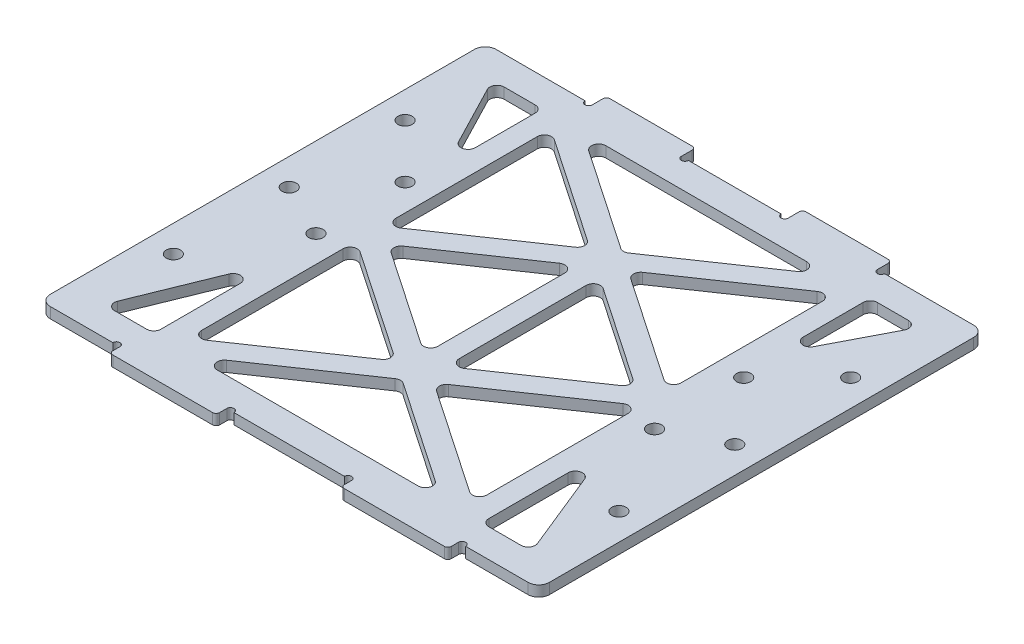
SolidWorks part; units mm, degrees
material "Thornel Mat VMA"
ref_plane "前视基准面" through (0, 0, 0) normal (0, 0, 1) x (1, 0, 0)
ref_plane "上视基准面" through (0, 0, 0) normal (0, 1, 0) x (1, 0, 0)
ref_plane "右视基准面" through (0, 0, 0) normal (1, 0, 0) x (0, 0, -1)
sketch "草图1" plane through (0, 0, 0) normal (0, 1, 0) x (1, 0, 0)
  line L0 (0, -55) -> (0, 55) construction
  line L29 (-17.5, 0) -> (17.5, 0)
  line L31 (-47.5, 0) -> (-47.5, -3)
  line L32 (-47.5, -3) -> (-17.5, -3)
  line L33 (-17.5, 0) -> (-17.5, -3)
  line L34 (17.5, 0) -> (17.5, -3)
  line L35 (47.5, -3) -> (17.5, -3)
  line L36 (47.5, 0) -> (47.5, -3)
  line L42 (47.5, 80) -> (-47.5, 80) construction
  line L43 (47.5, 80) -> (47.5, 55) construction
  line L44 (47.5, 55) -> (-47.5, 55) construction
  line L45 (-47.5, 80) -> (-47.5, 55) construction
  line L52 (-15, 125) -> (15, 125)
  line L63 (-70, 125) -> (-40, 125)
  line L64 (-40, 125) -> (-40, 129)
  line L65 (-40, 129) -> (-15, 129)
  line L66 (-15, 125) -> (-15, 129)
  line L67 (15, 125) -> (15, 129)
  line L68 (15, 129) -> (40, 129)
  line L69 (40, 129) -> (40, 125)
  line L70 (40, 125) -> (70, 125)
  line L72 (0, 55) -> (0, 0) construction
  line L82 (-70, 0) -> (-47.5, 0)
  line L87 (47.5, 0) -> (70, 0)
  line L90 (-18, 113) -> (18, 113) construction
  line L91 (-18, 113) -> (-18, 77) construction
  line L92 (-18, 77) -> (18, 77) construction
  line L93 (18, 113) -> (18, 77) construction
  line L94 (-70, 125) -> (-70, 0)
  line L95 (70, 125) -> (70, 0)
  line L96 (-62.5, 95) -> (-62.5, 30) construction
  circle A2 centre (47.5, 80) radius 2
  circle A3 centre (47.5, 55) radius 2
  circle A4 centre (-47.5, 55) radius 2
  circle A5 centre (-47.5, 80) radius 2
  circle A12 centre (18, 113) radius 1.5 construction
  circle A13 centre (18, 77) radius 1.5 construction
  circle A14 centre (-18, 77) radius 1.5 construction
  circle A15 centre (-18, 113) radius 1.5 construction
  circle A16 centre (-62.5, 30) radius 2
  circle A17 centre (-62.5, 62.5) radius 2
  circle A18 centre (-62.5, 95) radius 2
  circle A19 centre (62.5, 95) radius 2
  circle A20 centre (62.5, 62.5) radius 2
  circle A21 centre (62.5, 30) radius 2
  point P57 (0, 125)
  dimension "D16" = 30
  dimension "D20" = 4
  dimension "D31" = 12
  dimension "D32" = 3
  dimension "D43" = 4
  dimension "D13" = 65
  dimension "D14" = 4
  dimension "D15" = 125
  dimension "D5" = 3
  dimension "D6" = 30
  dimension "D7" = 35
  dimension "D8" = 140
  dimension "D9" = 7.5
  dimension "D10" = 25
  dimension "D11" = 30
  dimension "D12" = 45
  dimension "D18" = 25
  dimension "D19" = 95
  dimension "D30" = 36
extrude "凸台-拉伸1" add sketch "草图1" along normal blind 3
sketch "草图3" plane through (0, 3, 0) normal (0, 1, 0) x (1, 0, 0)
  line L10 (0, -1.65) -> (0, 1.65) construction
  line L11 (-60, 117) -> (-46, 90)
  line L16 (46, 8) -> (46, 42.5)
  line L26 (-40, 117) -> (40, 117)
  line L27 (60, 8) -> (46, 8)
  line L40 (46, 42.5) -> (60, 8)
  line L41 (-40, 117) -> (-40, 8)
  line L42 (-40, 8) -> (40, 8)
  line L44 (-46, 90) -> (-46, 117)
  line L45 (-46, 117) -> (-60, 117)
  line L47 (-46, 42.5) -> (-60, 8)
  line L48 (-60, 8) -> (-46, 8)
  line L49 (-46, 8) -> (-46, 42.5)
  line L51 (-17.5, 0) -> (17.5, 0) construction
  line L52 (15, 125) -> (-15, 125) construction
  line L53 (-70, 125) -> (-70, 0) construction
  line L54 (46, 117) -> (60, 117)
  line L55 (46, 90) -> (46, 117)
  line L56 (40, 117) -> (40, 8)
  line L57 (60, 117) -> (46, 90)
  circle A4 centre (-47.5, 80) radius 2 construction
  circle A5 centre (-47.5, 55) radius 2 construction
  dimension "D1" = 7.5
  dimension "D8" = 10
  dimension "D2" = 6
  dimension "D3" = 6
  dimension "D4" = 8
  dimension "D5" = 8
  dimension "D7" = 10
  dimension "D9" = 12.5
  dimension "D6" = 10
extrude "切除-拉伸2" cut sketch "草图3" against normal through all
sketch "草图2" plane through (0, 3, 0) normal (0, 1, 0) x (1, 0, 0)
  line L0 (15, 125) -> (-15, 125) construction
  line L1 (70, 125) -> (40, 125) construction
  line L13 (-17.5, 0) -> (17.5, 0) construction
  line L14 (-70, 0) -> (-47.5, 0) construction
  line L20 (-40, 125) -> (-70, 125) construction
  line L26 (15, 125) -> (-15, 125) construction
  line L30 (47.5, 0) -> (70, 0) construction
  circle A31 centre (-48.5, 0) radius 1
  circle A32 centre (-16.5, 0) radius 1
  circle A33 centre (16.5, 0) radius 1
  circle A37 centre (14, 125) radius 1
  circle A38 centre (-41, 125) radius 1
  circle A39 centre (-14, 125) radius 1
  circle A40 centre (41, 125) radius 1
  circle A65 centre (48.5, 0) radius 1
  dimension "D1" = 2
extrude "切除-拉伸1" cut sketch "草图2" against normal through all
sketch "草图5" plane through (0, 3, 0) normal (0, 1, 0) x (1, 0, 0)
  line L0 (-40, 117) -> (-40, 8) construction
  line L1 (40, 8) -> (40, 117) construction
  line L52 (-40, 117) -> (40, 62.5)
  line L54 (40, 62.5) -> (-40, 8)
  line L55 (40, 8) -> (-40, 62.5)
  line L57 (-40, 62.5) -> (40, 117)
  line L58 (0, 89.75) -> (0, 35.25)
extrude "拉伸-薄壁1" add sketch "草图5" against normal up to surface (3 mm away) thin up to face at (50.6667, 0, -108) thin type mid plane wall 6
fillet "圆角1" radius 2 36 edges at (40, 1.5, -58.87) (40, 1.5, -11.63) (34.6716, 1.5, -8) (-34.6716, 1.5, -8) (-40, 1.5, -11.63) (-40, 1.5, -58.87) (-40, 1.5, -66.13) (-34.6716, 1.5, -117) (34.6716, 1.5, -117) (40, 1.5, -113.37) (40, 1.5, -66.13) (-46, 1.5, -90) (-60, 1.5, -117) (-46, 1.5, -117) (-60, 1.5, -8) (-46, 1.5, -42.5) (-46, 1.5, -8) (46, 1.5, -42.5) (60, 1.5, -8) (46, 1.5, -8) (60, 1.5, -117) (46, 1.5, -90) (46, 1.5, -117) (-40, 1.5, -113.37) (34.6716, 1.5, -62.5) (3, 1.5, -84.0762) (3, 1.5, -40.9238) (-34.6716, 1.5, -62.5) (-3, 1.5, -40.9238) (5.3284, 1.5, -89.75) (0, 1.5, -31.62) (0, 1.5, -93.38) (-5.3284, 1.5, -35.25) (-5.3284, 1.5, -89.75) (5.3284, 1.5, -35.25) (-3, 1.5, -84.0762)
fillet "圆角2" radius 1 8 edges at (-47.5, 1.5, 3) (-17.5, 1.5, 3) (17.5, 1.5, 3) (47.5, 1.5, 3) (40, 1.5, -129) (15, 1.5, -129) (-15, 1.5, -129) (-40, 1.5, -129)
fillet "圆角3" radius 3 4 edges at (70, 1.5, -125) (70, 1.5, 0) (-70, 1.5, 0) (-70, 1.5, -125)
